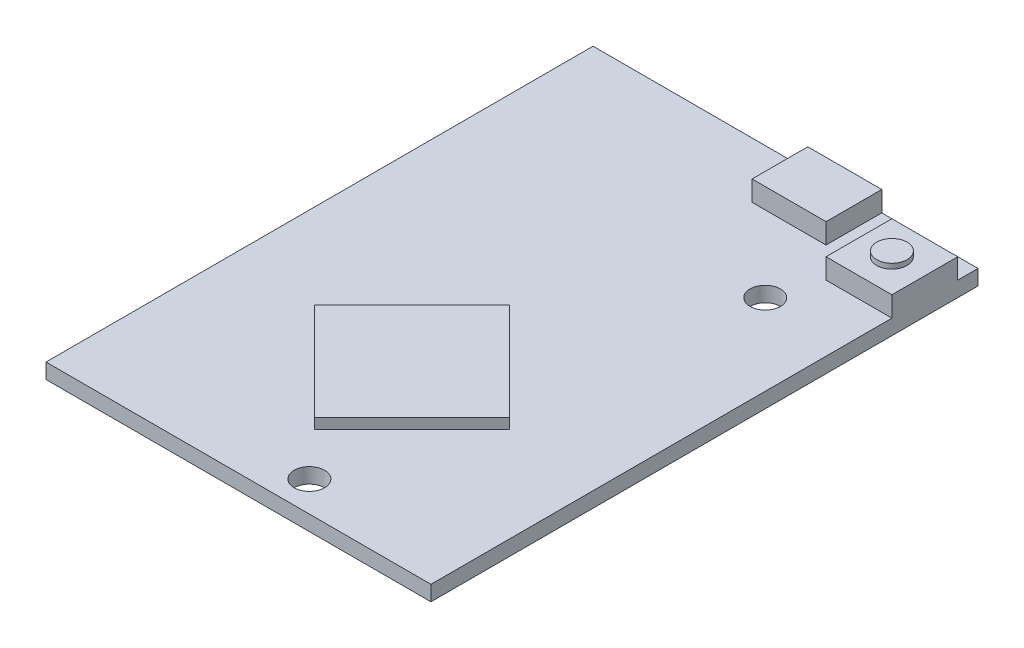
SolidWorks part; units mm, degrees
ref_plane "Front Plane" through (0, 0, 0) normal (0, 0, 1) x (1, 0, 0)
ref_plane "Top Plane" through (0, 0, 0) normal (0, 1, 0) x (1, 0, 0)
ref_plane "Right Plane" through (0, 0, 0) normal (1, 0, 0) x (0, 0, -1)
sketch "Sketch1" plane through (0, 0, 0) normal (0, 1, 0) x (1, 0, 0)
  line L1 (-19, 27) -> (19, 27)
  line L2 (-19, 27) -> (-19, -27)
  line L3 (-19, -27) -> (19, -27)
  line L4 (19, 27) -> (19, -27)
  line L5 (-19, 27) -> (19, -27) construction
  line L6 (-19, -27) -> (19, 27) construction
  point P0 (0, 0)
  dimension "D1" = 54
  dimension "D2" = 38
extrude "PCB" add sketch "Sketch1" along normal blind 1.5
sketch "Sketch2" plane through (0, 1.5, 0) normal (0, 1, 0) x (1, 0, 0)
  line L0 (0, -0.2667) -> (9.6167, -9.8833)
  line L1 (9.6167, -9.8833) -> (0, -19.5)
  line L2 (0, -19.5) -> (-9.6167, -9.8833)
  line L3 (-9.6167, -9.8833) -> (0, -0.2667)
  line L4 (-19, -27) -> (19, -27) construction
  dimension "D1" = 13.6
  dimension "D2" = 7.5
extrude "ATMega" add sketch "Sketch2" along normal blind 1
sketch "Sketch3" plane through (0, 1.5, 0) normal (0, 1, 0) x (1, 0, 0)
  line L0 (19, 27) -> (-19, 27) construction
  line L1 (2.2, 27) -> (9.5, 27)
  line L2 (2.2, 27) -> (2.2, 21.5)
  line L3 (2.2, 21.5) -> (9.5, 21.5)
  line L4 (9.5, 27) -> (9.5, 21.5)
  line L5 (19, -27) -> (19, 27) construction
  line L6 (19, 25) -> (12.5, 25)
  line L7 (19, 25) -> (19, 18.5)
  line L8 (19, 18.5) -> (12.5, 18.5)
  line L9 (12.5, 25) -> (12.5, 18.5)
  dimension "D1" = 7.3
  dimension "D2" = 5.5
  dimension "D3" = 9.5
  dimension "D4" = 6.5
  dimension "D5" = 2
extrude "USB and RST" add sketch "Sketch3" along normal blind 2
sketch "Sketch4" plane through (0, 3.5, 0) normal (0, 1, 0) x (1, 0, 0)
  line L0 (12.5, 25) -> (19, 18.5) construction
  circle A0 centre (15.75, 21.75) radius 1.5
  point P6 (15.75, 21.75)
  dimension "D1" = 3
extrude "Button" add sketch "Sketch4" along normal blind 0.5
sketch "Sketch5" plane through (0, 1.5, 0) normal (0, 1, 0) x (1, 0, 0)
  line L0 (19, -27) -> (19, 18.5) construction
  line L1 (-19, -27) -> (19, -27) construction
  circle A0 centre (11, 14) radius 1.5
  circle A1 centre (4, -24) radius 1.5
  dimension "D1" = 3
  dimension "D2" = 7
  dimension "D3" = 38
  dimension "D4" = 8
  dimension "D5" = 3
extrude "Cut-Extrude1" cut sketch "Sketch5" against normal through all both and the other way through all
